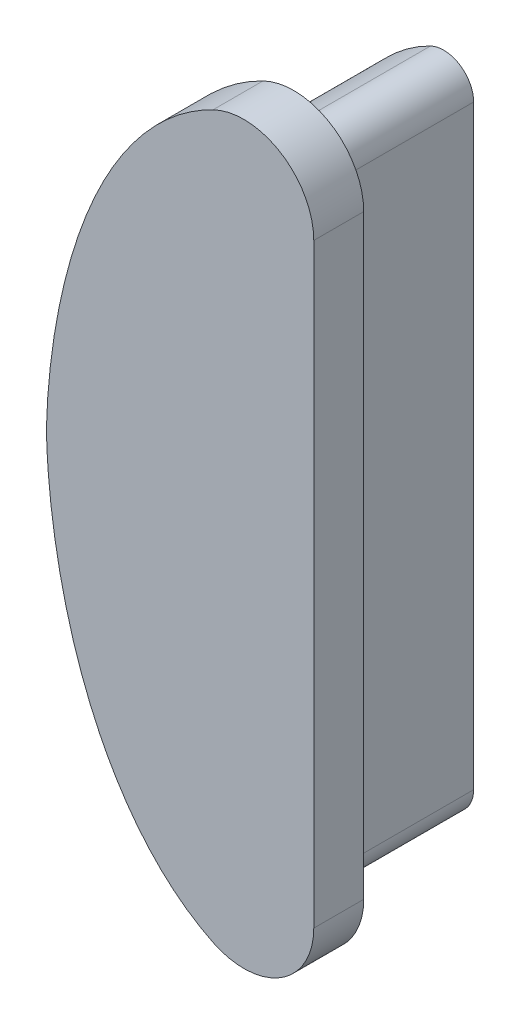
SolidWorks part; units mm, degrees
ref_plane "Front Plane" through (0, 0, 0) normal (0, 0, 1) x (1, 0, 0)
ref_plane "Top Plane" through (0, 0, 0) normal (0, 1, 0) x (1, 0, 0)
ref_plane "Right Plane" through (0, 0, 0) normal (1, 0, 0) x (0, 0, -1)
sketch "Sketch1" plane through (0, 0, 0) normal (0, 0, 1) x (1, 0, 0)
  line L0 (2.8137, -7.2337) -> (2.8137, 6.3125)
  line L2 (3.0637, -7.513) -> (3.0637, 6.5917) construction
  spline S0 degree 3 poles (3.0637, 6.5917) (0.0622, 6.3847) (-1.12, 2.403) (-1.189, -0.4606) knots 0 0 0 0 1 1 1 1 construction
  spline S1 degree 3 poles (3.0637, -7.513) (0.0622, -7.306) (-1.12, -3.3243) (-1.189, -0.4606) knots 0 0 0 0 1 1 1 1 construction
  spline S2 degree 1 poles (2.8137, 6.3125) (-0.9389, -0.4606) knots 0 0 1 1 construction
  spline S3 degree 1 poles (2.8137, -7.2337) (-0.9389, -0.4606) knots 0 0 1 1 construction
  spline S4 degree 3 poles (2.8137, 6.3125) (2.5047, 6.2644) (1.8935, 6.0648) (0.8901, 5.3424) (-0.0809, 3.8988) (-0.6473, 2.0733) (-0.8822, 0.5819) (-0.9302, -0.1077) (-0.9389, -0.4606) knots 0.032675 0.032675 0.032675 0.032675 0.153501 0.274327 0.515979 0.757631 0.878457 0.999283 0.999283 0.999283 0.999283
  spline S5 degree 3 poles (-0.9389, -0.4606) (-0.9302, -0.8136) (-0.8822, -1.5031) (-0.6473, -2.9946) (-0.0809, -4.8201) (0.8901, -6.2637) (1.8935, -6.9861) (2.5047, -7.1857) (2.8137, -7.2337) knots 0.032675 0.032675 0.032675 0.032675 0.153501 0.274327 0.515979 0.757631 0.878457 0.999283 0.999283 0.999283 0.999283
  point P9 (3.0637, -0.4606)
  dimension "D1" = 0.25
extrude "Boss-Extrude1" add sketch "Sketch1" along normal blind 3
fillet "Fillet1" radius 0.6 2 edges at (2.8137, -7.2337, 1.5) (2.8137, 6.3125, 1.5)
sketch "Sketch3" plane through (0, 0, 3) normal (0, 0, 1) x (1, 0, 0)
  line L2 (3.6137, -6.4212) -> (3.6137, 5.4999)
  line L3 (3.6137, -6.4212) -> (3.6137, 5.4999)
  arc A4 (1.597, -7.678) -> (3.6137, -6.4212) centre (2.2137, -6.4212) ccw
  arc A5 (3.6137, 5.4999) -> (1.597, 6.7568) centre (2.2137, 5.4999) ccw
  arc A6 (1.597, -7.678) -> (3.6137, -6.4212) centre (2.2137, -6.4212) ccw
  arc A7 (3.6137, 5.4999) -> (1.597, 6.7568) centre (2.2137, 5.4999) ccw
  spline S4 degree 3 poles (4925.7314, 826.7088) (588.2504, 219.3619) (-15.1353, 70.537) (-1.4583, -2.8652) (-1.3808, -3.2048) (-1.1968, -3.8699) (-0.9837, -4.5233) (-0.7017, -5.1488) (-0.376, -5.7565) (-0.1892, -6.0545) (0.2312, -6.6088) (0.4641, -6.8656) (0.8587, -7.2101) (0.9982, -7.318) (26.6844, -24.5879) (245.0473, 260.005) (2770.0165, 4154.4309) knots -26.56071 -26.56071 -26.56071 -26.56071 0.25 0.25 0.375 0.375 0.5 0.625 0.625 0.75 0.75 0.875 0.875 0.9375 0.9375 11.950603 11.950603 11.950603 11.950603 only from (-1.7392, -0.4606) to (1.597, -7.678)
  spline S5 degree 3 poles (2890.0706, -4073.1778) (205.0019, -191.2713) (22.5134, 25.1451) (0.4675, 5.9479) (0.2338, 5.6904) (-0.1841, 5.1406) (-0.3702, 4.8453) (-0.6993, 4.2328) (-0.8412, 3.9183) (-1.0899, 3.2765) (-1.1966, 2.9492) (-1.3807, 2.2839) (-1.4582, 1.9447) (-15.305, -72.3499) (603.6426, -221.0748) (4929.0999, -807.8058) knots -10.201448 -10.201448 -10.201448 -10.201448 0.125 0.125 0.25 0.25 0.375 0.375 0.5 0.5 0.625 0.625 0.75 0.75 27.870529 27.870529 27.870529 27.870529 only from (1.597, 6.7568) to (-1.7392, -0.4606)
  spline S6 degree 3 poles (-1.7392, -0.4606) (-1.722, -1.1554) (-1.6487, -1.8432) (-1.4583, -2.8652) (-1.3808, -3.2048) (-1.1968, -3.8699) (-0.9837, -4.5233) (-0.7017, -5.1488) (-0.376, -5.7565) (-0.1892, -6.0545) (0.2312, -6.6088) (0.4641, -6.8656) (0.8587, -7.2101) (0.9982, -7.318) (1.2881, -7.5129) (1.4392, -7.6006) (1.597, -7.678) knots 0 0 0 0 0.25 0.25 0.375 0.375 0.5 0.625 0.625 0.75 0.75 0.875 0.875 0.9375 0.9375 1 1 1 1
  spline S7 degree 3 poles (1.597, 6.7568) (1.2821, 6.6022) (0.9948, 6.4071) (0.4675, 5.9479) (0.2338, 5.6904) (-0.1841, 5.1406) (-0.3702, 4.8453) (-0.6993, 4.2328) (-0.8412, 3.9183) (-1.0899, 3.2765) (-1.1966, 2.9492) (-1.3807, 2.2839) (-1.4582, 1.9447) (-1.6487, 0.9221) (-1.722, 0.2341) (-1.7392, -0.4606) knots 0 0 0 0 0.125 0.125 0.25 0.25 0.375 0.375 0.5 0.5 0.625 0.625 0.75 0.75 1 1 1 1
  dimension "D1" = 0.8
extrude "Boss-Extrude2" add sketch "Sketch3" along normal blind 1
